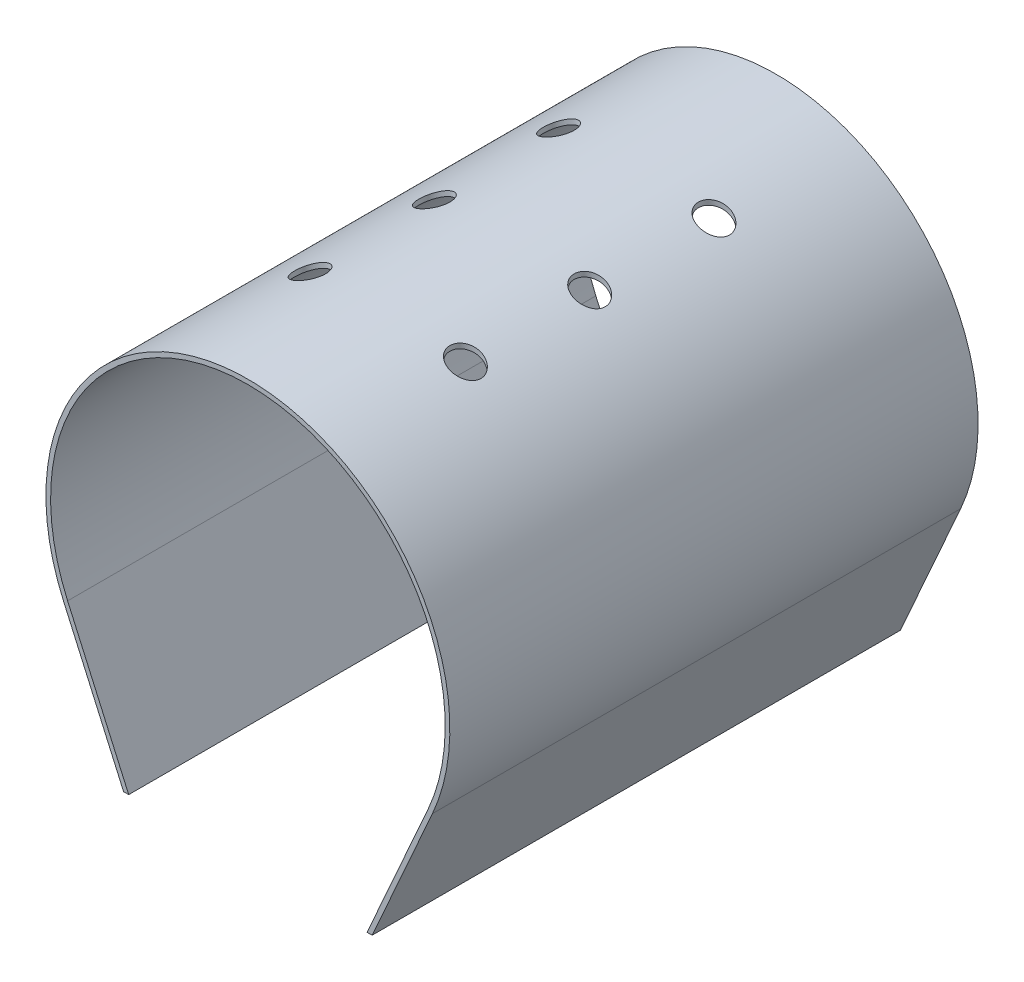
SolidWorks part; units mm, degrees
ref_plane "Front Plane" through (0, 0, 0) normal (0, 0, 1) x (1, 0, 0)
ref_plane "Top Plane" through (0, 0, 0) normal (0, 1, 0) x (1, 0, 0)
ref_plane "Right Plane" through (0, 0, 0) normal (1, 0, 0) x (0, 0, -1)
sketch "Sketch1" plane through (0, 0, 0) normal (0, 0, 1) x (1, 0, 0)
  line L0 (-59.3879, 43.5788) -> (-40, 0)
  line L1 (40, 0) -> (59.3879, 43.5788)
  line L2 (38.6295, 0.6097) -> (58.0174, 44.1885)
  line L3 (-58.0174, 44.1885) -> (-38.6295, 0.6097)
  line L4 (-38.6295, 0.6097) -> (-38.3583, 0)
  line L5 (38.6295, 0.6097) -> (38.3583, 0)
  line L6 (-40, 0) -> (-38.3583, 0)
  line L7 (38.3583, 0) -> (40, 0)
  arc A0 (59.3879, 43.5788) -> (-59.3879, 43.5788) centre (0, 70) ccw
  arc A1 (58.0174, 44.1885) -> (-58.0174, 44.1885) centre (0, 70) ccw
  point P7 (0, 0)
  dimension "D1" = 130
  dimension "D2" = 70
  dimension "D3" = 80
  dimension "D4" = 40
  dimension "D5" = 1.5
extrude "Boss-Extrude1" add sketch "Sketch1" along normal blind 170
ref_plane "Plane1" through (0, 70, 0) normal (0, 1, 0) x (1, 0, 0)
sketch "Sketch2" plane through (0, 70, 0) normal (0, 1, 0) x (1, 0, 0)
  circle A0 centre (-25, -45) radius 5
  circle A1 centre (25, -45) radius 5
  circle A2 centre (25, -85) radius 5
  circle A3 centre (25, -125) radius 5
  circle A4 centre (-25, -85) radius 5
  circle A5 centre (-25, -125) radius 5
  dimension "D1" = 10
  dimension "D3" = 45
  dimension "D2" = 25
  dimension "D4" = 2
  dimension "D5" = 3
extrude "Cut-Extrude1" cut sketch "Sketch2" along normal through all
